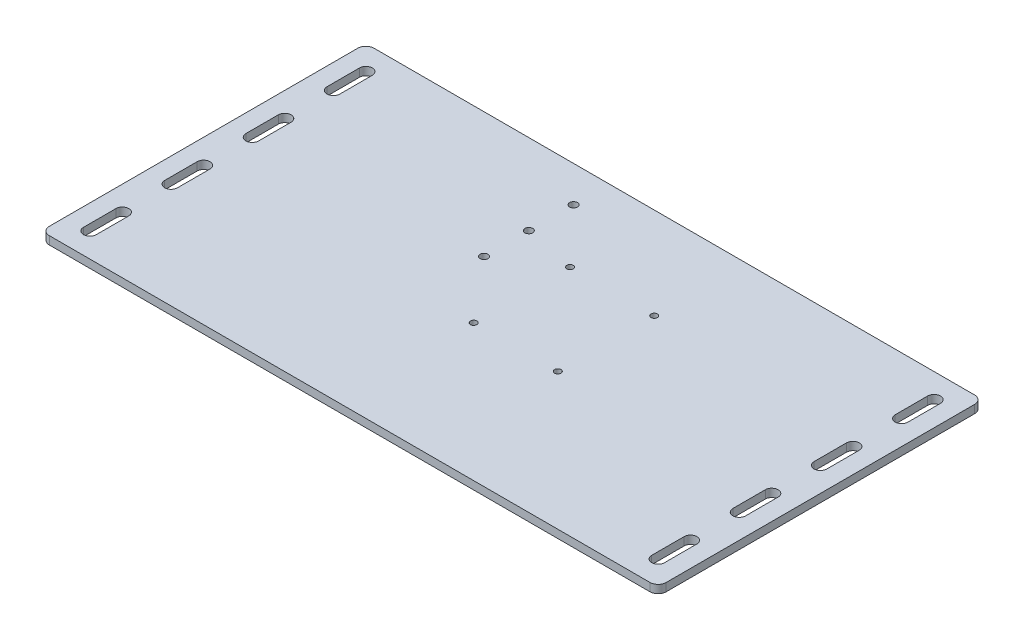
SolidWorks part; units mm, degrees
material "6061-T6 (SS)"
ref_plane "Front Plane" through (0, 0, 0) normal (0, 0, 1) x (1, 0, 0)
ref_plane "Top Plane" through (0, 0, 0) normal (0, 1, 0) x (1, 0, 0)
ref_plane "Right Plane" through (0, 0, 0) normal (1, 0, 0) x (0, 0, -1)
sketch "Sketch1" plane through (0, 0, 0) normal (0, 1, 0) x (1, 0, 0)
  line L1 (-241.3, 127) -> (241.3, 127)
  line L2 (-241.3, 127) -> (-241.3, -127)
  line L3 (-241.3, -127) -> (241.3, -127)
  line L4 (241.3, 127) -> (241.3, -127)
  line L5 (-241.3, 127) -> (241.3, -127) construction
  line L6 (-241.3, -127) -> (241.3, 127) construction
  point P0 (0, 0)
  dimension "D1" = 482.6
  dimension "D2" = 254
extrude "Boss-Extrude1" add sketch "Sketch1" along normal mid plane 6.35
fillet "Fillet1" radius 6.35 4 edges at (-241.3, 0, 127) (-241.3, 0, -127) (241.3, 0, -127) (241.3, 0, 127)
sketch "Sketch2" plane through (0, 3.175, 0) normal (0, 1, 0) x (1, 0, 0)
  line L0 (222.25, 127) -> (222.25, -127) construction
  line L1 (234.95, 127) -> (-234.95, 127) construction
  line L2 (-234.95, -127) -> (234.95, -127) construction
  line L3 (0, 0) -> (222.25, 0) construction
  line L4 (111.125, 0) -> (111.125, -127) construction
  line L5 (111.125, -63.5) -> (222.25, -63.5) construction
  line L6 (166.6875, -63.5) -> (166.6875, -127) construction
  line L7 (222.25, -82.55) -> (222.25, -107.95) construction
  line L8 (227.25, -82.55) -> (227.25, -107.95)
  line L9 (217.25, -82.55) -> (217.25, -107.95)
  line L10 (222.25, 44.45) -> (222.25, 19.05) construction
  line L13 (222.25, -44.45) -> (222.25, -19.05) construction
  line L14 (227.25, -44.45) -> (227.25, -19.05)
  line L15 (217.25, -44.45) -> (217.25, -19.05)
  line L16 (227.25, 44.45) -> (227.25, 19.05)
  line L17 (217.25, 44.45) -> (217.25, 19.05)
  line L18 (222.25, 82.55) -> (222.25, 107.95) construction
  line L19 (227.25, 82.55) -> (227.25, 107.95)
  line L20 (217.25, 82.55) -> (217.25, 107.95)
  line L21 (0, -3.4925) -> (0, 3.4925) construction
  line L22 (-222.25, 82.55) -> (-222.25, 107.95) construction
  line L23 (-227.25, 82.55) -> (-227.25, 107.95)
  line L24 (-217.25, 82.55) -> (-217.25, 107.95)
  line L25 (-222.25, 44.45) -> (-222.25, 19.05) construction
  line L26 (-227.25, 44.45) -> (-227.25, 19.05)
  line L27 (-217.25, 44.45) -> (-217.25, 19.05)
  line L28 (-222.25, -44.45) -> (-222.25, -19.05) construction
  line L29 (-227.25, -44.45) -> (-227.25, -19.05)
  line L30 (-217.25, -44.45) -> (-217.25, -19.05)
  line L31 (-222.25, -82.55) -> (-222.25, -107.95) construction
  line L32 (-227.25, -82.55) -> (-227.25, -107.95)
  line L33 (-217.25, -82.55) -> (-217.25, -107.95)
  arc A0 (227.25, -82.55) -> (217.25, -82.55) centre (222.25, -82.55) ccw
  arc A1 (217.25, -107.95) -> (227.25, -107.95) centre (222.25, -107.95) ccw
  arc A4 (227.25, -44.45) -> (217.25, -44.45) centre (222.25, -44.45) cw
  arc A5 (217.25, -19.05) -> (227.25, -19.05) centre (222.25, -19.05) cw
  arc A6 (227.25, 44.45) -> (217.25, 44.45) centre (222.25, 44.45) ccw
  arc A7 (217.25, 19.05) -> (227.25, 19.05) centre (222.25, 19.05) ccw
  arc A8 (227.25, 82.55) -> (217.25, 82.55) centre (222.25, 82.55) cw
  arc A9 (217.25, 107.95) -> (227.25, 107.95) centre (222.25, 107.95) cw
  arc A10 (-227.25, 82.55) -> (-217.25, 82.55) centre (-222.25, 82.55) ccw
  arc A11 (-217.25, 107.95) -> (-227.25, 107.95) centre (-222.25, 107.95) ccw
  arc A12 (-227.25, 44.45) -> (-217.25, 44.45) centre (-222.25, 44.45) cw
  arc A13 (-217.25, 19.05) -> (-227.25, 19.05) centre (-222.25, 19.05) cw
  arc A14 (-227.25, -44.45) -> (-217.25, -44.45) centre (-222.25, -44.45) ccw
  arc A15 (-217.25, -19.05) -> (-227.25, -19.05) centre (-222.25, -19.05) ccw
  arc A16 (-227.25, -82.55) -> (-217.25, -82.55) centre (-222.25, -82.55) cw
  arc A17 (-217.25, -107.95) -> (-227.25, -107.95) centre (-222.25, -107.95) cw
  point P17 (222.25, -95.25)
  point P23 (166.6875, -95.25)
  point P26 (222.25, 31.75)
  point P33 (222.25, -31.75)
  point P40 (222.25, 95.25)
  point P49 (-222.25, 95.25)
  point P56 (-222.25, 31.75)
  point P63 (-222.25, -31.75)
  point P70 (-222.25, -95.25)
  dimension "D2" = 5
  dimension "D1" = 222.25
  dimension "D3" = 25.4
extrude "Cut-Extrude1" cut sketch "Sketch2" against normal up to next
sketch "Sketch3" plane through (0, 3.175, 0) normal (0, 1, 0) x (1, 0, 0)
  circle A0 centre (-50.8, 98.956) radius 3.05 construction
  circle A1 centre (-50.8, 98.956) radius 3.05
  circle A2 centre (-50.8, 63.956) radius 3.05 construction
  circle A3 centre (-50.8, 63.956) radius 3.05
  circle A4 centre (-50.8, 28.956) radius 3.05 construction
  circle A5 centre (-50.8, 28.956) radius 3.05
extrude "Cut-Extrude2" cut sketch "Sketch3" against normal through all
sketch "Sketch4" plane through (0, 3.175, 0) normal (0, -1, 0) x (1, 0, 0)
  circle A0 centre (55.8992, 20.0497) radius 2.5 construction
  circle A1 centre (55.8992, 20.0497) radius 2.5
  circle A2 centre (-9.9295, 20.0497) radius 2.5 construction
  circle A3 centre (-9.9295, 20.0497) radius 2.5
  circle A4 centre (55.9129, -55.3503) radius 2.5 construction
  circle A5 centre (55.9129, -55.3503) radius 2.5
  circle A6 centre (-9.9434, -55.3636) radius 2.5 construction
  circle A7 centre (-9.9434, -55.3636) radius 2.5
extrude "Cut-Extrude3" cut sketch "Sketch4" along normal blind 10
equation "\"width\"=482.6"
equation "\"height\"=254"
equation "\"D1@Sketch1\"=\"width\""
equation "\"D2@Sketch1\"=\"height\""
